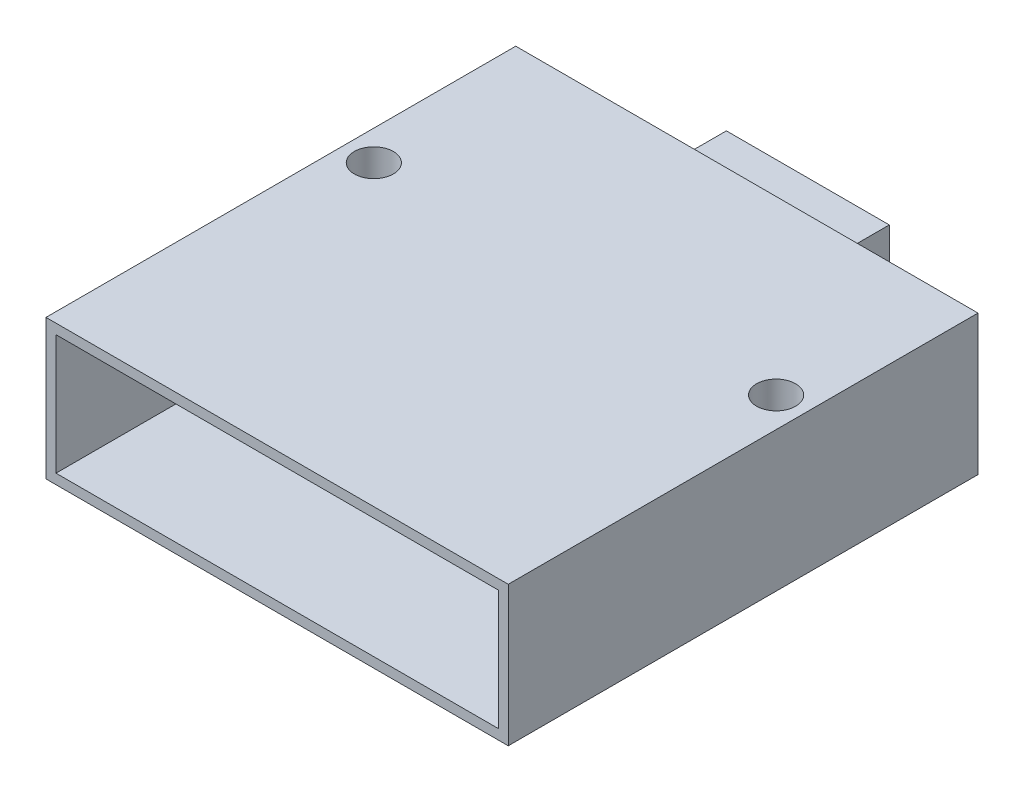
SolidWorks part; units mm, degrees
material "PVC Rigid"
ref_plane "Front Plane" through (0, 0, 0) normal (0, 0, 1) x (1, 0, 0)
ref_plane "Top Plane" through (0, 0, 0) normal (0, 1, 0) x (1, 0, 0)
ref_plane "Right Plane" through (0, 0, 0) normal (1, 0, 0) x (0, 0, -1)
sketch "Sketch1" plane through (0, 0, 0) normal (0, 0, 1) x (1, 0, 0)
  line L1 (-58.7375, -17.78) -> (58.7375, -17.78)
  line L2 (-58.7375, -17.78) -> (-58.7375, 17.78)
  line L3 (-58.7375, 17.78) -> (58.7375, 17.78)
  line L4 (58.7375, -17.78) -> (58.7375, 17.78)
  line L5 (-58.7375, -17.78) -> (58.7375, 17.78) construction
  line L6 (-58.7375, 17.78) -> (58.7375, -17.78) construction
  point P0 (0, 0)
  dimension "D1" = 117.475
  dimension "D2" = 35.56
extrude "Extrude1" add sketch "Sketch1" along normal blind 119.38
sketch "Sketch2" plane through (0, 0, 0) normal (0, 0, -1) x (-1, 0, 0)
  line L1 (-20.701, -10.414) -> (20.701, -10.414)
  line L2 (-20.701, -10.414) -> (-20.701, 10.414)
  line L3 (-20.701, 10.414) -> (20.701, 10.414)
  line L4 (20.701, -10.414) -> (20.701, 10.414)
  line L5 (-20.701, -10.414) -> (20.701, 10.414) construction
  line L6 (-20.701, 10.414) -> (20.701, -10.414) construction
  point P0 (0, 0)
  dimension "D1" = 20.828
  dimension "D2" = 41.402
extrude "Extrude2" add sketch "Sketch2" along normal blind 15.494
sketch "Sketch3" plane through (0, -17.78, 0) normal (0, -1, 0) x (1, 0, 0)
  line L0 (-51.1175, 0) -> (-51.1175, 43.688) construction
  line L1 (-58.7375, 0) -> (58.7375, 0) construction
  line L2 (-51.1175, 43.688) -> (-58.7375, 43.688) construction
  line L3 (-58.7375, 119.38) -> (-58.7375, 0) construction
  line L4 (51.1175, 0) -> (51.1175, 43.688) construction
  line L5 (51.1175, 43.688) -> (58.7375, 43.688) construction
  line L6 (58.7375, 119.38) -> (58.7375, 0) construction
  dimension "D1" = 43.688
  dimension "D2" = 7.62
hole_wizard "25/64 (0.39063) Diameter Hole1" positions "3DSketch1" profile "Sketch5" hole size "25/64" standard "Ansi Inch" end condition through all
sketch3d "3DSketch1"
  point P0 (-51.1175, -17.78, 43.688)
  point P3 (51.1175, -17.78, 43.688)
sketch "Sketch5" plane through (-51.1175, -17.78, 43.688) normal (1, 0, 0) x (0, 0, -1)
  line L0 (0, 0) -> (0, 35.56)
  line L1 (0, 35.56) -> (4.961, 35.56)
  line L2 (4.961, 35.56) -> (4.961, 0)
  line L5 (4.961, 0) -> (0, 0)
  line L11 (0, -6.35) -> (0, 107.95) construction
  dimension "Thru Hole Dia." = 9.922
  dimension "Thru Hole Depth" = 35.56
sketch "Sketch6" plane through (0, 0, -15.494) normal (0, 0, -1) x (-1, 0, 0)
  point P0 (0, 0)
sketch "Sketch7" plane through (0, 0, 119.38) normal (0, 0, 1) x (1, 0, 0)
  point P0 (0, 0)
shell "Shell1" thickness 2.54
